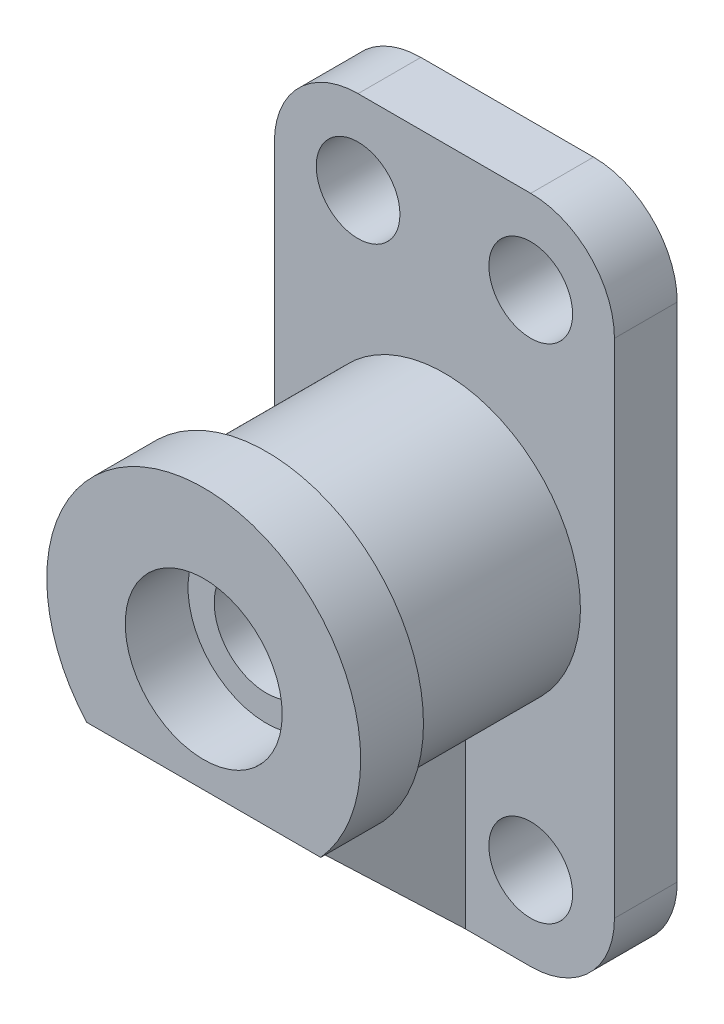
SolidWorks part; units mm, degrees
ref_plane "Ön Düzlem" through (0, 0, 0) normal (0, 0, 1) x (1, 0, 0)
ref_plane "Üst Düzlem" through (0, 0, 0) normal (0, 1, 0) x (1, 0, 0)
ref_plane "Sağ Düzlem" through (0, 0, 0) normal (1, 0, 0) x (0, 0, -1)
sketch "Çizim1" plane through (0, 0, 0) normal (0, 0, 1) x (1, 0, 0)
  line L0 (-85.1677, 82.3133) -> (-85.1677, -13.6867)
  line L1 (-69.1677, 98.3133) -> (-36.1677, 98.3133)
  line L2 (-20.1677, 82.3133) -> (-20.1677, -13.6867)
  line L3 (-36.1677, -29.6867) -> (-69.1677, -29.6867)
  arc A0 (-69.1677, 98.3133) -> (-85.1677, 82.3133) centre (-69.1677, 82.3133) ccw
  arc A1 (-20.1677, 82.3133) -> (-36.1677, 98.3133) centre (-36.1677, 82.3133) ccw
  arc A2 (-36.1677, -29.6867) -> (-20.1677, -13.6867) centre (-36.1677, -13.6867) ccw
  arc A3 (-85.1677, -13.6867) -> (-69.1677, -29.6867) centre (-69.1677, -13.6867) ccw
  circle A4 centre (-69.1677, 82.3133) radius 8
  circle A5 centre (-36.1677, 82.3133) radius 8
  circle A6 centre (-69.1677, -13.6867) radius 8
  circle A7 centre (-36.1677, -13.6867) radius 8
  dimension "D1" = 32
  dimension "D2" = 32
  dimension "D3" = 32
  dimension "D4" = 32
  dimension "D5" = 16
  dimension "D6" = 16
  dimension "D7" = 16
  dimension "D8" = 16
  dimension "D9" = 16
  dimension "D10" = 128
  dimension "D11" = 33
extrude "Yükseklik-Ekstrüzyon2" add sketch "Çizim1" along normal blind 12
sketch "Çizim2" plane through (0, 0, 12) normal (0, 0, 1) x (1, 0, 0)
  line L0 (-36.1677, 98.3133) -> (-69.1677, 98.3133) construction
  line L1 (-20.1677, -13.6867) -> (-20.1677, 82.3133) construction
  circle A0 centre (-52.6677, 34.3133) radius 26
  circle A1 centre (-52.6677, 34.3133) radius 10
  dimension "D3" = 20
  dimension "D4" = 52
  dimension "D1" = 64
  dimension "D2" = 32.5
extrude "Yükseklik-Ekstrüzyon3" add sketch "Çizim2" along normal blind 34
sketch "Çizim3" plane through (0, 0, 12) normal (0, 0, 1) x (1, 0, 0)
  circle A0 centre (-52.6677, 34.3133) radius 10
extrude "Kes-Ekstrüzyon1" cut sketch "Çizim3" against normal blind 34
sketch "Çizim4" plane through (0, 0, 46) normal (0, 0, 1) x (1, 0, 0)
  circle A0 centre (-52.6677, 34.3133) radius 30
  circle A1 centre (-52.6677, 34.3133) radius 15
  dimension "D1" = 60
  dimension "D2" = 30
extrude "Yükseklik-Ekstrüzyon4" add sketch "Çizim4" along normal blind 12
sketch "Çizim6" plane through (0, 0, 58) normal (0, 0, 1) x (1, 0, 0)
  line L1 (-75.0284, 14.3133) -> (-27.539, 14.3133)
  line L2 (-75.0284, 14.3133) -> (-75.0284, 0.062)
  line L3 (-75.0284, 0.062) -> (-27.539, 0.062)
  line L4 (-27.539, 14.3133) -> (-27.539, 0.062)
  circle A0 centre (-52.6677, 34.3133) radius 30 construction
  circle A1 centre (-52.6677, 34.3133) radius 10 construction
  dimension "D1" = 20
extrude "Kes-Ekstrüzyon2" cut sketch "Çizim6" against normal blind 46
ref_plane "Düzlem1" through (-52.6677, 0, 0) normal (-1, 0, 0) x (0, 0, 1)
sketch "Çizim9" plane through (-52.6677, 0, 0) normal (-1, 0, 0) x (0, 0, 1)
  line L0 (58, 14.3133) -> (12, -29.6867)
rib "Feder1" sketch "Çizim9" sketch "Çizim9" thickness 8 extrusion direction parallel to sketch draft on no parameters "D1"=8
